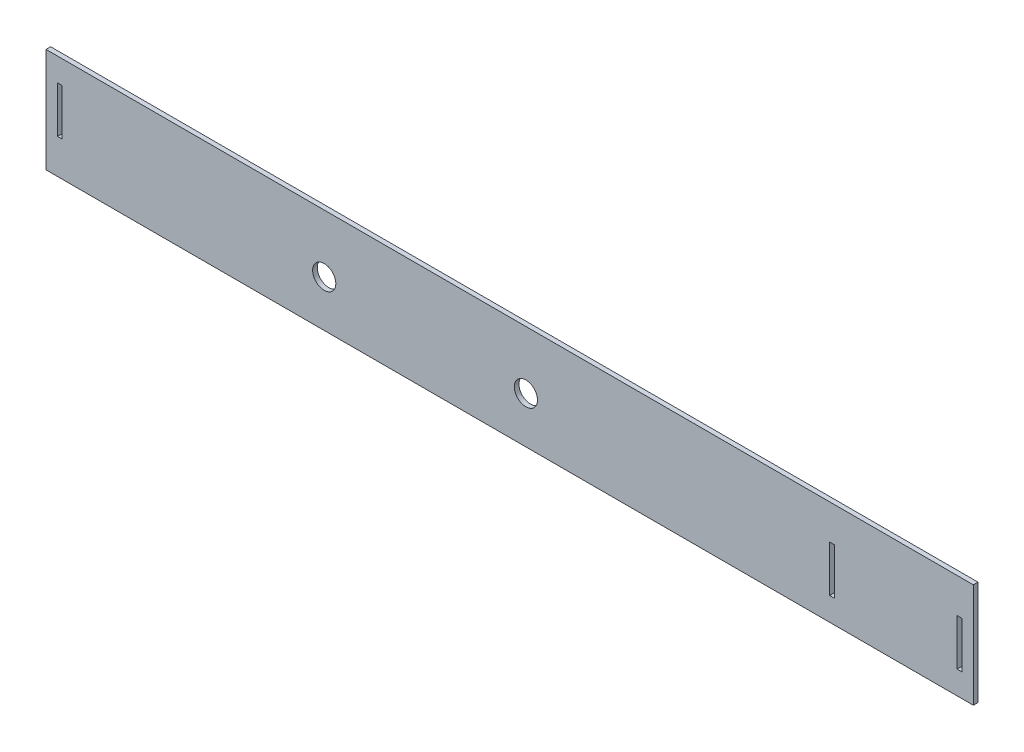
SolidWorks part; units mm, degrees
ref_plane "Спереди" through (0, 0, 0) normal (0, 0, 1) x (1, 0, 0)
ref_plane "Сверху" through (0, 0, 0) normal (0, 1, 0) x (1, 0, 0)
ref_plane "Справа" through (0, 0, 0) normal (1, 0, 0) x (0, 0, -1)
sketch "Эскиз1" plane through (0, 0, 0) normal (0, 0, 1) x (1, 0, 0)
  line L1 (0, 0) -> (400, 0)
  line L2 (0, 0) -> (0, 45)
  line L3 (0, 45) -> (400, 45)
  line L4 (400, 0) -> (400, 45)
  line L5 (338, 30) -> (340, 30)
  line L6 (338, 30) -> (338, 10)
  line L7 (338, 10) -> (340, 10)
  line L8 (340, 30) -> (340, 10)
  line L13 (5, 35) -> (7, 35)
  line L14 (5, 35) -> (5, 15)
  line L15 (5, 15) -> (7, 15)
  line L16 (7, 35) -> (7, 15)
  line L17 (393, 30) -> (395, 30)
  line L18 (393, 30) -> (393, 10)
  line L19 (393, 10) -> (395, 10)
  line L20 (395, 30) -> (395, 10)
  circle A0 centre (120, 20) radius 5
  circle A1 centre (207, 20) radius 5
  dimension "D5" = 10
  dimension "D6" = 10
  dimension "D1" = 400
  dimension "D2" = 45
  dimension "D3" = 120
  dimension "D4" = 207
  dimension "D7" = 2
  dimension "D9" = 20
  dimension "D11" = 60
  dimension "D13" = 10
  dimension "D14" = 25
  dimension "D15" = 25
  dimension "D16" = 2
  dimension "D17" = 20
  dimension "D18" = 10
  dimension "D19" = 5
  dimension "D8" = 2
  dimension "D10" = 5
  dimension "D12" = 20
  dimension "D20" = 10
extrude "Бобышка-Вытянуть1" add sketch "Эскиз1" along normal blind 2
equation "\"D4@Эскиз1\"=107+100"
